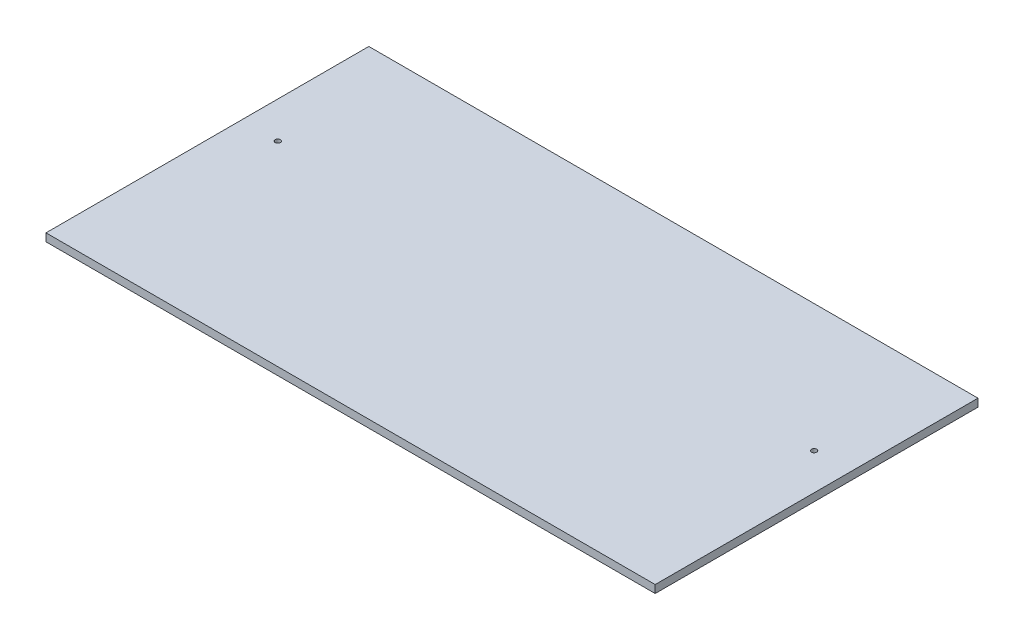
SolidWorks part; units mm, degrees
material "Balsa"
ref_plane "Front Plane" through (0, 0, 0) normal (0, 0, 1) x (1, 0, 0)
ref_plane "Top Plane" through (0, 0, 0) normal (0, 1, 0) x (1, 0, 0)
ref_plane "Right Plane" through (0, 0, 0) normal (1, 0, 0) x (0, 0, -1)
sketch "Sketch1" plane through (0, 0, 0) normal (0, 1, 0) x (1, 0, 0)
  line L1 (-371.475, -196.85) -> (371.475, -196.85)
  line L2 (-371.475, -196.85) -> (-371.475, 196.85)
  line L3 (-371.475, 196.85) -> (371.475, 196.85)
  line L4 (371.475, -196.85) -> (371.475, 196.85)
  line L5 (-371.475, -196.85) -> (371.475, 196.85) construction
  line L6 (-371.475, 196.85) -> (371.475, -196.85) construction
  point P0 (0, 0)
  dimension "D1" = 393.7
  dimension "D2" = 742.95
extrude "Boss-Extrude1" add sketch "Sketch1" along normal blind 9.525
sketch "Sketch2" plane through (0, 9.525, 0) normal (0, 1, 0) x (1, 0, 0)
  line L0 (-96.4917, 58.8642) -> (-50.7811, 58.8642)
  line L1 (-50.7811, 58.8642) -> (-50.7811, -117.2841)
  line L2 (57.7088, 162.8799) -> (157.0484, 162.8799)
  line L3 (53.9298, -46.6515) -> (53.9298, 58.8642)
  line L4 (53.9298, 58.8642) -> (96.2888, 58.8642)
  dimension "D1" = 19.05
  dimension "D2" = 19.05
  dimension "D3" = 19.05
  dimension "D4" = 19.05
other "TTLogo-3"
sketch_block "TTLogo" parameters "D1"=79.3277, "D2"=51.944, "D3"=51.944, "D4"=516.7732, "D5"=516.7732
extrude "Cut-Extrude2" [suppressed] cut sketch "Sketch2" against normal blind 3.175
fillet "Fillet1" [suppressed] radius 6.35
sketch "Sketch3" plane through (0, 9.525, 0) normal (0, 1, 0) x (1, 0, 0)
  line L0 (-371.475, 196.85) -> (-371.475, -196.85) construction
  line L1 (-371.475, -196.85) -> (371.475, -196.85) construction
  line L2 (371.475, -196.85) -> (371.475, 196.85) construction
  circle A0 centre (-327.025, 41.402) radius 3.175
  circle A1 centre (327.025, 41.402) radius 3.175
  dimension "D1" = 6.35
  dimension "D2" = 44.45
  dimension "D3" = 238.252
  dimension "D4" = 6.35
  dimension "D5" = 44.45
  dimension "D6" = 238.252
extrude "Cut-Extrude3" cut sketch "Sketch3" against normal through all
